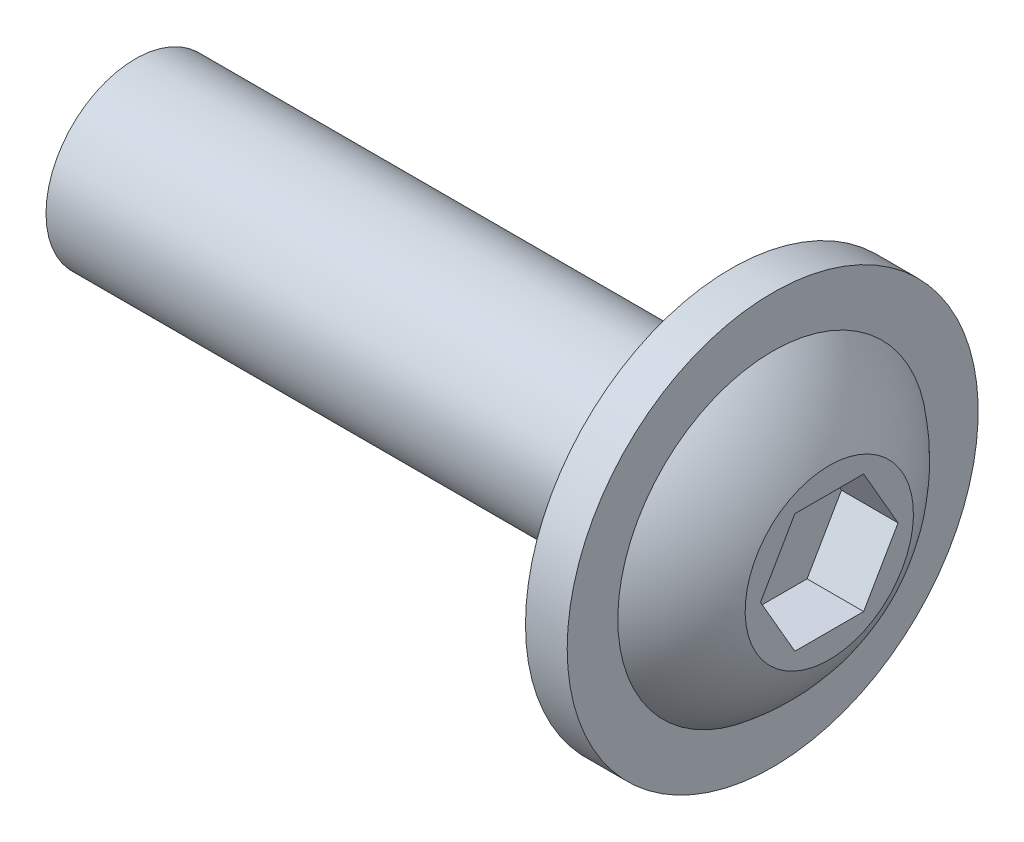
SolidWorks part; units mm, degrees
material "1.7220 (34CrMo4)"
ref_plane "Front" through (0, 0, 0) normal (0, 0, 1) x (1, 0, 0)
ref_plane "Top" through (0, 0, 0) normal (0, 1, 0) x (1, 0, 0)
ref_plane "Right" through (0, 0, 0) normal (1, 0, 0) x (0, 0, -1)
sketch "Sketch1" plane through (0, 0, 0) normal (0, 0, 1) x (1, 0, 0)
  line L0 (0, 0) -> (1.1027, 0) construction
  line L1 (0, 0) -> (0, 1.4129)
  line L2 (-0.95, 2.6) -> (-0.95, 3.45)
  line L3 (-0.95, 3.45) -> (-1.65, 3.45)
  line L4 (-1.65, 3.45) -> (-1.65, 1.5)
  line L5 (-1.65, 1.5) -> (-11.65, 1.5)
  line L6 (-11.65, 1.5) -> (-11.65, 0)
  line L7 (-11.65, 0) -> (0, 0)
  line L8 (-11.65, 1.25) -> (-11.15, 1.25) construction
  line L10 (-11.15, 0) -> (-11.15, 1.5) construction
  arc A1 (-0.95, 2.6) -> (0, 1.4129) centre (-2.9822, 0) cw
  point P13 (-11.15, 1.25)
  dimension "r1 min" = 3.3
  dimension "dc max" = 6.9
  dimension "dk max" = 5.2
  dimension "c max" = 0.7
  dimension "M" = 3
  dimension "L" = 10
  dimension "M minor" = 2.5
  dimension "P" = 0.5
revolve "Revolve1" add sketch "Sketch1" angle 360 about L0
cosmetic thread "Cosmetic Thread1" parameters "D1"=9, "D2"=2.5
sketch "Sketch2" plane through (0, 0, 0) normal (1, 0, 0) x (0, 0, -1)
  line L1 (1.1547, 0) -> (0.5774, 1)
  line L2 (0.5774, 1) -> (-0.5774, 1)
  line L3 (-0.5774, 1) -> (-1.1547, 0)
  line L4 (-1.1547, 0) -> (-0.5774, -1)
  line L5 (-0.5774, -1) -> (0.5774, -1)
  line L6 (0.5774, -1) -> (1.1547, 0)
  circle A0 centre (0, 0) radius 1 construction
  dimension "s" = 2
extrude "Cut-Extrude1" cut sketch "Sketch2" against normal up to surface (0.95 mm away) up to face at (-0.95, 0, 3.45)
equation "\"D2@Cosmetic Thread1\"=\"M minor@Sketch1\""
equation "\"D1@Cosmetic Thread1\"=\"L@Sketch1\"-2*\"P@Sketch1\""
